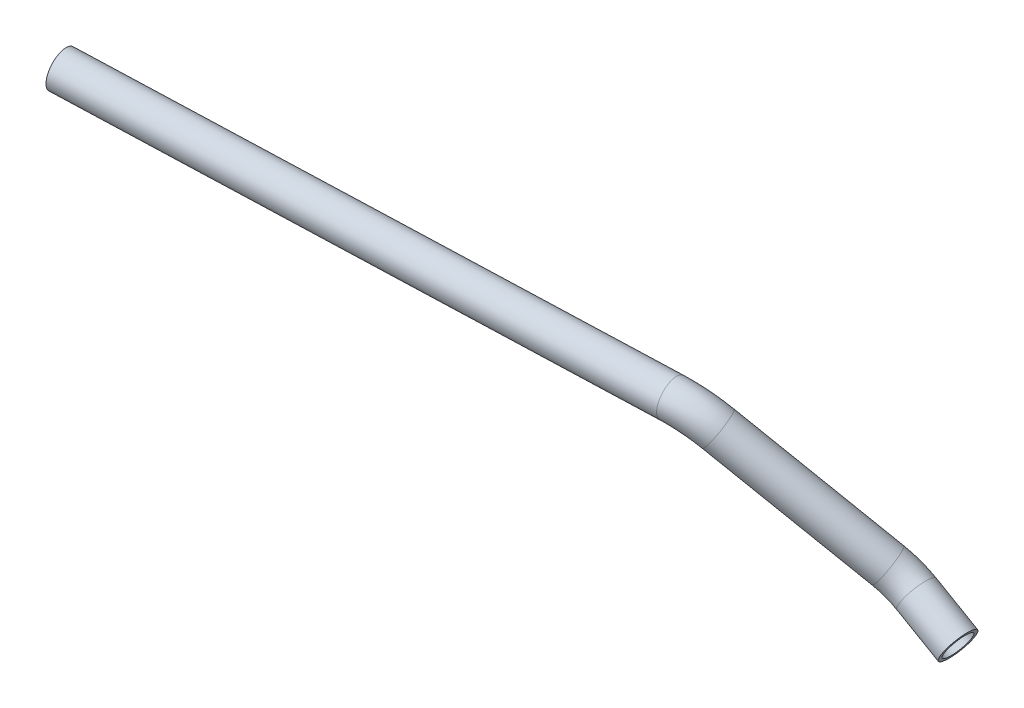
SolidWorks part; units mm, degrees
ref_plane "Plan de face" through (0, 0, 0) normal (0, 0, 1) x (1, 0, 0)
ref_plane "Plan de dessus" through (0, 0, 0) normal (0, 1, 0) x (1, 0, 0)
ref_plane "Plan de droite" through (0, 0, 0) normal (1, 0, 0) x (0, 0, -1)
sketch3d "Esquisse3D1"
  line L0 (0, 0, 0) -> (-10.2698, 5.9293, 0)
  line L1 (0, 0, 0) -> (-346.2496, 0, 0) construction
  line L2 (0, 0, 0) -> (12.9904, -7.5, 0)
  line L3 (-17.3205, 10, 0) -> (-95, 72, 0) construction
  line L4 (0, 0, 0) -> (0, 279.9718, 0) construction
  line L5 (-95, 72, 0) -> (-95, 72, 39) construction
  line L6 (-23.2439, 14.7278, 2.9739) -> (-86.4804, 65.2, 34.7226)
  line L7 (0, 0, 0) -> (-400, 110, 0) construction
  line L8 (-400, 110, 0) -> (-400, 110, 89) construction
  line L9 (-106.4692, 73.429, 40.8802) -> (-400, 110, 89)
  arc A0 (-106.4692, 73.429, 40.8802) -> (-86.4804, 65.2, 34.7226) centre (-113.6835, 37.9783, 23.8154) ccw
  arc A1 (-23.2439, 14.7278, 2.9739) -> (-10.2698, 5.9293, 0) centre (-3.1513, 18.2589, 37.3806) ccw
  point P12 (-95, 72, 39)
  point P14 (-117.2933, 55.8509, -11.7872)
  point P17 (-17.3205, 10, 0)
  point P19 (-21.8416, -14.1136, 51.6176)
  dimension "D10" = 40
  dimension "D11" = 40
  dimension "D1" = 30
  dimension "D3" = 15
  dimension "D2" = 20
  dimension "D4" = 72
  dimension "D6" = 39
  dimension "D5" = 95
  dimension "D7" = 400
  dimension "D9" = 89
  dimension "D8" = 110
ref_plane "Plan1" through (-400, 110, 89) normal (-0.9795, 0.122, 0.1606) x (0.1593, -0.0199, 0.987)
sketch "Esquisse1" plane through (-400, 110, 89) normal (-0.9795, 0.122, 0.1606) x (0.1593, -0.0199, 0.987)
  circle A0 centre (0, 0) radius 10
  circle A1 centre (0, 0) radius 8
  dimension "D1" = 20
  dimension "D2" = 16
sweep "Balayage1" add profiles "Esquisse1" path "Esquisse3D1"
sketch "Esquisse3" plane through (0, 0, 0) normal (0, 0, 1) x (1, 0, 0)
  line L0 (-10.2698, 5.9293) -> (12.9904, -7.5) construction
  line L1 (7.9904, -16.1603) -> (17.9904, 1.1603) construction
  circle A0 centre (6.0622, -3.5) radius 2
  dimension "D2" = 4
  dimension "D1" = 8
extrude "Extrusion1" add sketch "Esquisse3" along normal up to next and the other way up to next
